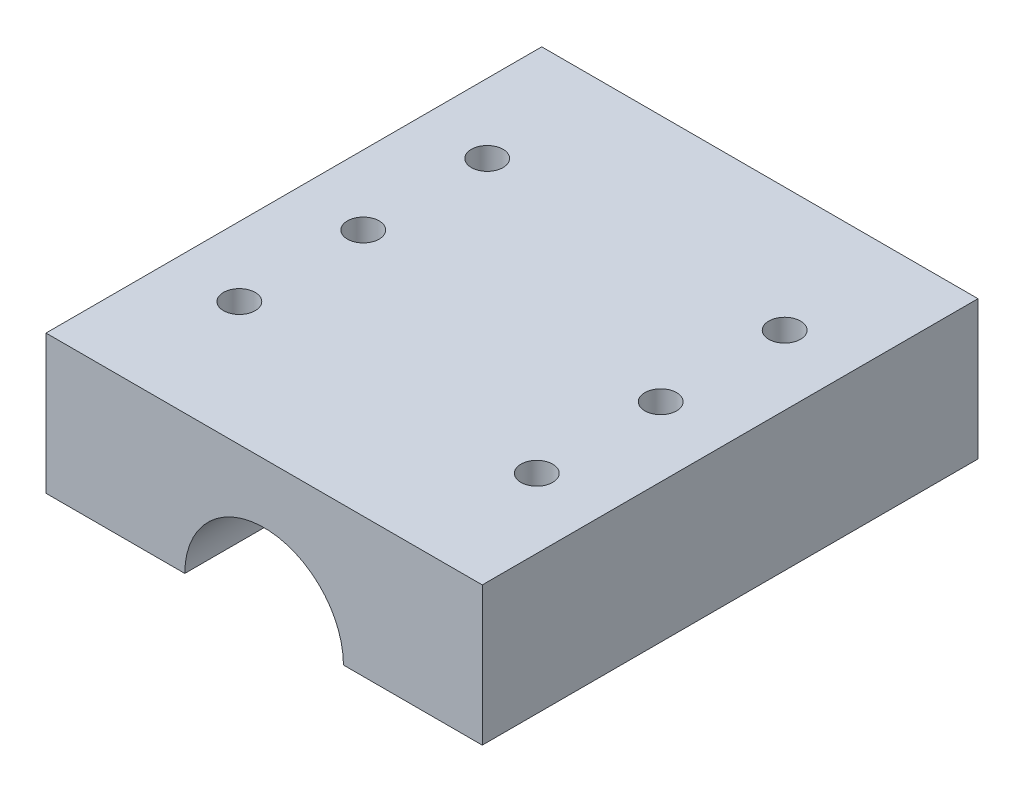
SolidWorks part; units mm, degrees
ref_plane "Ön Düzlem" through (0, 0, 0) normal (0, 0, 1) x (1, 0, 0)
ref_plane "Üst Düzlem" through (0, 0, 0) normal (0, 1, 0) x (1, 0, 0)
ref_plane "Sağ Düzlem" through (0, 0, 0) normal (1, 0, 0) x (0, 0, -1)
sketch "Çizim1" plane through (0, 0, 0) normal (0, 0, 1) x (1, 0, 0)
  line L0 (-404.9243, 0) -> (19841.2884, 0) construction
  line L1 (-8, 0) -> (-22, 0)
  line L2 (-22, 0) -> (-22, 14)
  line L3 (-22, 14) -> (22, 14)
  line L5 (22, 0) -> (22, 14)
  line L6 (8, 0) -> (22, 0)
  arc A0 (8, 0) -> (-8, 0) centre (0, 0) ccw
  dimension "D1" = 16
  dimension "D2" = 44
  dimension "D3" = 22
  dimension "D4" = 14
  dimension "D5" = 22
  dimension "D6" = 14
extrude "Yükseklik-Ekstrüzyon1" add sketch "Çizim1" against normal blind 50
sketch "Çizim2" plane through (0, 14, 0) normal (0, 1, 0) x (1, 0, 0)
  line L0 (0, 0) -> (0, 50) construction
  line L1 (22, 50) -> (-22, 50) construction
  line L2 (-22, 50) -> (-8, 50) construction
  line L3 (-8, 50) -> (-15, 50) construction
  line L4 (22, 0) -> (-22, 0) construction
  line L5 (-8, 50) -> (-8, 0) construction
  line L6 (-15, 50) -> (-15, 0) construction
  line L7 (15, 50) -> (15, 0) construction
  circle A6 centre (-15, 25) radius 1.6
  circle A7 centre (-15, 37.5) radius 1.6
  circle A8 centre (-15, 12.5) radius 1.6
  circle A9 centre (15, 12.5) radius 1.6
  circle A10 centre (15, 37.5) radius 1.6
  circle A11 centre (15, 25) radius 1.6
  dimension "D2" = 12.5
  dimension "D1" = 3.2
  dimension "D3" = 12.5
  dimension "D5" = 8
extrude "Kes-Ekstrüzyon1" cut sketch "Çizim2" against normal through all
